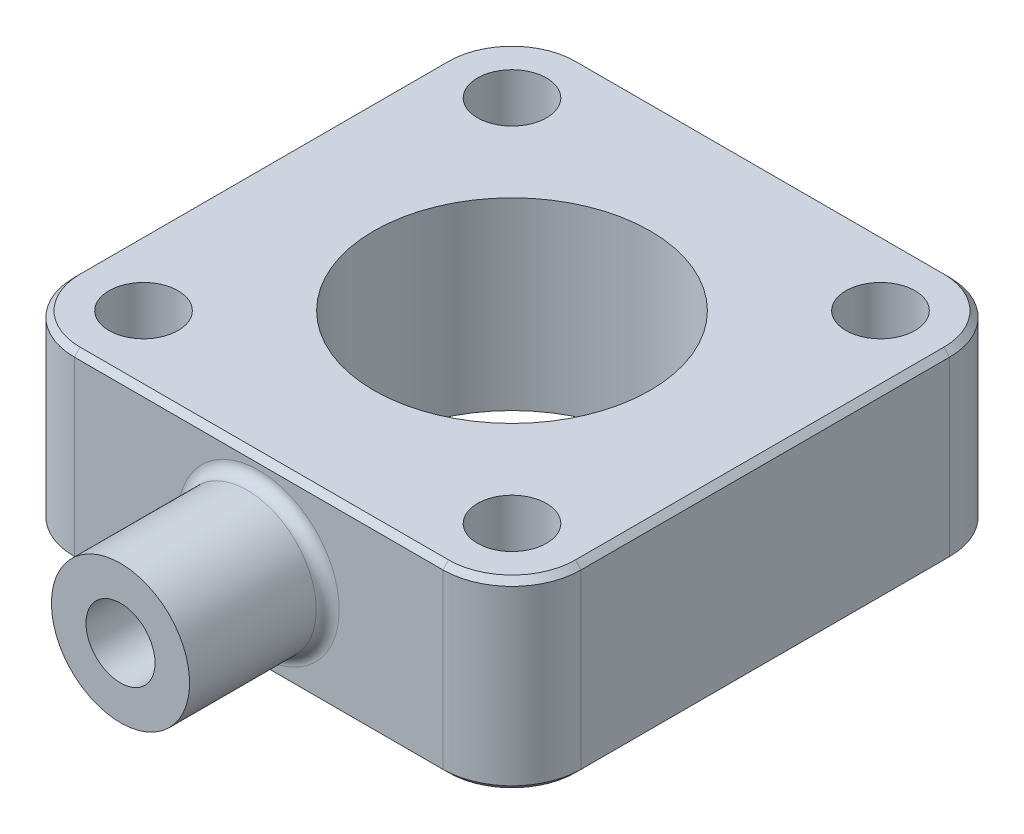
SolidWorks part; units mm, degrees
ref_plane "Front Plane" through (0, 0, 0) normal (0, 0, 1) x (1, 0, 0)
ref_plane "Top Plane" through (0, 0, 0) normal (0, 1, 0) x (1, 0, 0)
ref_plane "Right Plane" through (0, 0, 0) normal (1, 0, 0) x (0, 0, -1)
sketch "Sketch1" plane through (0, 0, 0) normal (0, 1, 0) x (1, 0, 0)
  line L1 (8, -11) -> (-8, -11)
  line L2 (11, -8) -> (11, 8)
  line L3 (8, 11) -> (-8, 11)
  line L4 (-11, -8) -> (-11, 8)
  line L5 (11, -11) -> (-11, 11) construction
  line L6 (11, 11) -> (-11, -11) construction
  arc A0 (8, -11) -> (11, -8) centre (8, -8) ccw
  arc A1 (-8, -11) -> (-11, -8) centre (-8, -8) cw
  arc A2 (11, 8) -> (8, 11) centre (8, 8) ccw
  arc A3 (-8, 11) -> (-11, 8) centre (-8, 8) ccw
  circle A4 centre (-8, 8) radius 1.5
  circle A5 centre (8, 8) radius 1.5
  circle A6 centre (8, -8) radius 1.5
  circle A7 centre (-8, -8) radius 1.5
  circle A8 centre (0, 0) radius 6
  point P0 (0, 0)
  dimension "D3" = 3
  dimension "D4" = 3
  dimension "D5" = 12
  dimension "D1" = 11
  dimension "D2" = 11
extrude "Boss-Extrude1" add sketch "Sketch1" along normal mid plane 8
sketch "Sketch2" plane through (0, 0, 0) normal (0, 0, 1) x (1, 0, 0)
  circle A0 centre (0, 0) radius 3
  dimension "D1" = 6
extrude "Boss-Extrude2" add sketch "Sketch2" along normal blind 6 from surface at 11 starting at face at (0, 0, 11)
sketch "Sketch3" plane through (0, 0, 17) normal (0, 0, 1) x (1, 0, 0)
  circle A0 centre (0, 0) radius 1.5
  dimension "D1" = 3
extrude "Cut-Extrude1" cut sketch "Sketch3" against normal blind 16
chamfer "Chamfer1" distance 0.25 angle 45 16 edges at (0, -4, -11) (-10.1213, -4, -10.1213) (10.1213, -4, -10.1213) (-11, -4, 0) (11, -4, 0) (-10.1213, -4, 10.1213) (10.1213, -4, 10.1213) (0, -4, 11) (0, 4, -11) (-10.1213, 4, -10.1213) (10.1213, 4, -10.1213) (-11, 4, 0) (11, 4, 0) (-10.1213, 4, 10.1213) (10.1213, 4, 10.1213) (0, 4, 11)
fillet "Fillet1" radius 0.5 1 edges at (-3, 0, 11)
